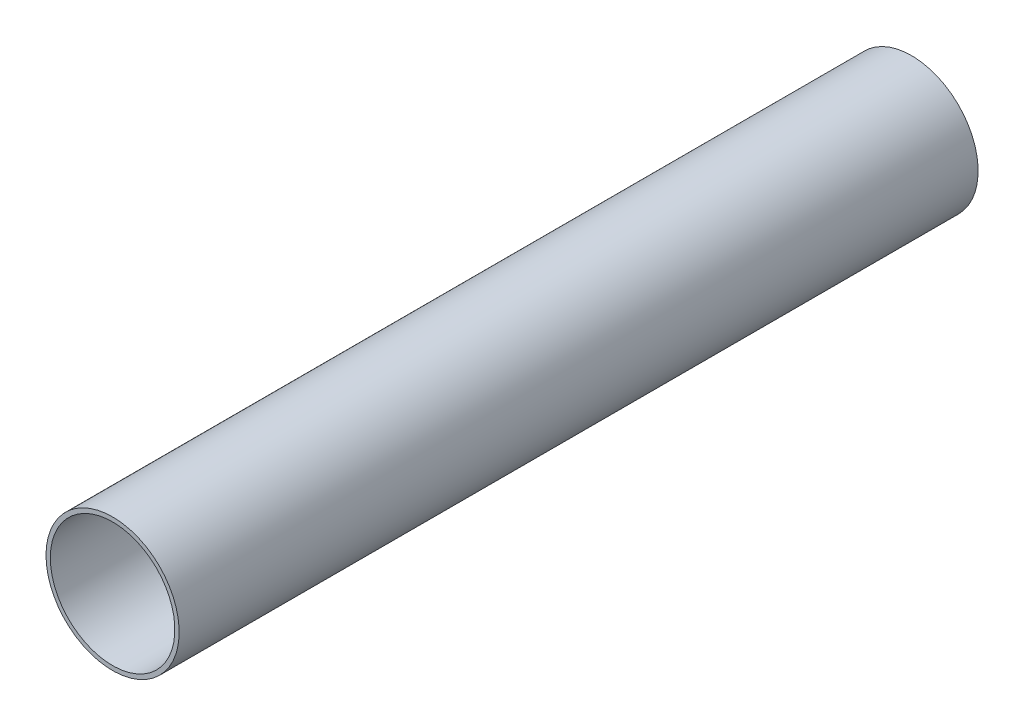
SolidWorks part; units mm, degrees
ref_plane "Front Plane" through (0, 0, 0) normal (0, 0, 1) x (1, 0, 0)
ref_plane "Top Plane" through (0, 0, 0) normal (0, 1, 0) x (1, 0, 0)
ref_plane "Right Plane" through (0, 0, 0) normal (1, 0, 0) x (0, 0, -1)
sketch "Sketch1" plane through (0, 0, 0) normal (0, 0, 1) x (1, 0, 0)
  circle A0 centre (0, 0) radius 25.4 construction
  circle A1 centre (0, 0) radius 23.749 construction
  point P3 (-25.4, 0)
  point P4 (25.4, 0)
  point P6 (-23.749, 0)
  point P7 (23.749, 0)
  dimension "OD" = 50.8
  dimension "Wall" = 1.651
  dimension "ID" = 47.498
sketch "Sketch2" plane through (0, 0, 0) normal (1, 0, 0) x (0, 0, -1)
  line L0 (152.4, 0) -> (-152.4, 0) construction
  line L2 (0, 25.4) -> (0, -25.4) construction
  line L3 (0, 25.4) -> (0, -25.4) construction
  line L4 (152.4, 25.4) -> (-152.4, 25.4) construction
  line L5 (152.4, -25.4) -> (-152.4, -25.4) construction
  line L6 (-152.4, -25.4) -> (-152.4, 25.4) construction
  line L7 (152.4, -25.4) -> (152.4, 25.4) construction
  line L8 (-101.6, -25.4) -> (-101.6, 25.4) construction
  line L9 (101.6, -25.4) -> (101.6, 25.4) construction
  point P3 (0, 0)
  point P9 (0, 25.4)
  point P11 (0, -25.4)
  point P13 (-152.4, 0)
  point P14 (152.4, 25.4)
  point P15 (-152.4, -25.4)
  point P16 (-152.4, 25.4)
  point P17 (-152.4, 0)
  point P18 (152.4, -25.4)
  point P19 (152.4, 0)
  point P22 (-101.6, 0)
  point P25 (101.6, 0)
  point P26 (-101.6, -25.4)
  point P27 (-101.6, 25.4)
  point P28 (101.6, 25.4)
  point P29 (101.6, -25.4)
  dimension "Length" = 304.8
  dimension "D1" = 50.8
sketch "Sketch3" plane through (0, 0, 0) normal (0, 0, 1) x (1, 0, 0)
  circle A0 centre (0, 0) radius 25.4 construction
  circle A1 centre (0, 0) radius 23.749 construction
  circle A2 centre (0, 0) radius 25.4
  circle A3 centre (0, 0) radius 23.749
extrude "Boss-Extrude1" add sketch "Sketch3" along normal mid plane 304.8
equation "\"D1@Sketch2\"=\"OD@Sketch1\""
equation "\"D1@Boss-Extrude1\"=\"Length@Sketch2\""
